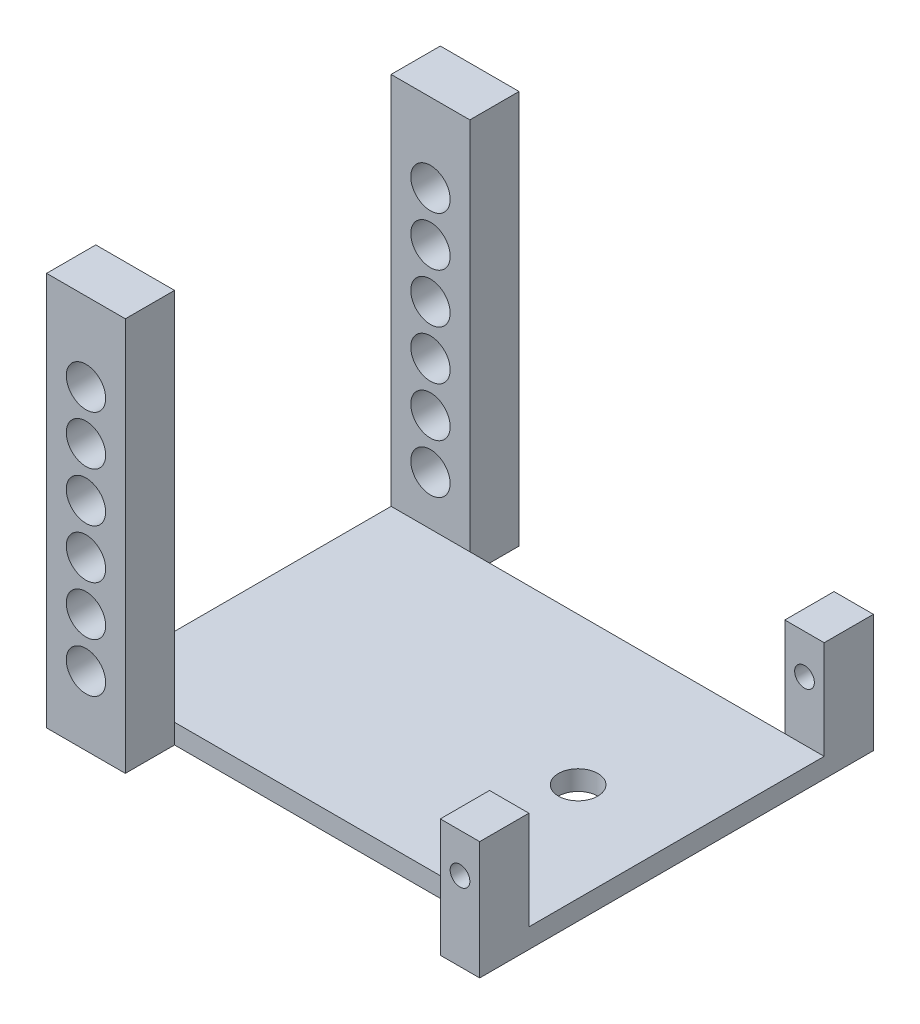
SolidWorks part; units mm, degrees
ref_plane "Front Plane" through (0, 0, 0) normal (0, 0, 1) x (1, 0, 0)
ref_plane "Top Plane" through (0, 0, 0) normal (0, 1, 0) x (1, 0, 0)
ref_plane "Right Plane" through (0, 0, 0) normal (1, 0, 0) x (0, 0, -1)
sketch "Sketch1" plane through (0, 0, 0) normal (0, 1, 0) x (1, 0, 0)
  line L1 (-100, 75) -> (100, 75)
  line L2 (-100, 75) -> (-100, -75)
  line L3 (-100, -75) -> (100, -75)
  line L4 (100, 75) -> (100, -75)
  line L5 (-100, 75) -> (100, -75) construction
  line L6 (-100, -75) -> (100, 75) construction
  point P0 (0, 0)
  dimension "D1" = 150
  dimension "D2" = 200
extrude "Boss-Extrude1" add sketch "Sketch1" along normal blind 10
sketch "Sketch2" plane through (0, 10, 0) normal (0, 1, 0) x (1, 0, 0)
  line L0 (100, -75) -> (100, 75) construction
  line L1 (-100, -75) -> (100, -75) construction
  line L2 (100, 75) -> (-100, 75) construction
  circle A0 centre (50, 0) radius 10
  point P6 (106.6698, -42.9521)
  dimension "D1" = 20
  dimension "D2" = 50
  dimension "D3" = 75
  dimension "D4" = 75
extrude "Cut-Extrude1" cut sketch "Sketch2" against normal blind 10
sketch "Sketch3" plane through (0, 0, 75) normal (0, 0, 1) x (1, 0, 0)
  line L0 (100, 0) -> (100, 60)
  line L1 (100, 60) -> (80, 60)
  line L2 (80, 60) -> (80, 0)
  line L3 (-100, 0) -> (100, 0) construction
  line L4 (80, 0) -> (100, 0)
  line L6 (-100, 200) -> (-120, 200)
  line L7 (-120, 200) -> (-120, 0)
  line L8 (-120, 0) -> (-100, 0)
  line L9 (-100, 200) -> (-80, 200)
  line L10 (-80, 200) -> (-80, 0)
  line L11 (-80, 0) -> (-100, 0)
  dimension "D1" = 20
  dimension "D2" = 60
  dimension "D3" = 200
  dimension "D4" = 20
  dimension "D5" = 20
sketch "Sketch4" plane through (-100, 0, 0) normal (-1, 0, 0) x (0, 0, 1)
  line L1 (-75, 10) -> (75, 10)
  line L2 (-75, 10) -> (-75, 0)
  line L3 (-75, 0) -> (75, 0)
  line L4 (75, 10) -> (75, 0)
  line L5 (-75, 10) -> (75, 0) construction
  line L6 (-75, 0) -> (75, 10) construction
  line L7 (-75, 10) -> (75, 10) construction
  line L8 (-75, 10) -> (-75, 0) construction
  point P0 (0, 5)
  dimension "D1" = 0
  dimension "D2" = 0
extrude "Boss-Extrude2" add sketch "Sketch4" along normal blind 20
extrude "Boss-Extrude3" add sketch "Sketch3" along normal blind 25
sketch "Sketch5" plane through (0, 0, -75) normal (0, 0, -1) x (-1, 0, 0)
  line L0 (-100, 0) -> (-100, 60)
  line L1 (-100, 60) -> (-80, 60)
  line L2 (-80, 60) -> (-80, 0)
  line L3 (-80, 0) -> (-100, 0)
  line L12 (80, 200) -> (120, 200)
  line L13 (120, 200) -> (120, 0)
  line L14 (120, 0) -> (80, 0)
  line L15 (80, 0) -> (80, 200)
  dimension "D1" = 60
extrude "Boss-Extrude4" add sketch "Sketch5" along normal blind 25
sketch "Sketch7" plane through (0, 0, -100) normal (0, 0, -1) x (-1, 0, 0)
  line L0 (-100, 0) -> (-80, 0) construction
  circle A0 centre (-90, 40) radius 5
  dimension "D1" = 10
  dimension "D2" = 40
extrude "Cut-Extrude3" cut sketch "Sketch7" against normal blind 251
sketch "Sketch9" plane through (0, 0, 100) normal (0, 0, 1) x (1, 0, 0)
  line L0 (-120, 0) -> (-80, 0) construction
  line L1 (-80, 0) -> (-80, 200) construction
  circle A0 centre (-100, 160) radius 10
  circle A1 centre (-100, 135) radius 10
  circle A2 centre (-100, 110) radius 10
  circle A3 centre (-100, 85) radius 10
  circle A5 centre (-100, 35) radius 10
  circle A6 centre (-100, 60) radius 10
  dimension "D1" = 20
  dimension "D7" = 20
  dimension "D8" = 20
  dimension "D9" = 20
  dimension "D10" = 20
  dimension "D11" = 20
  dimension "D2" = 160
  dimension "D3" = 20
  dimension "D4" = 25
  dimension "D5" = 25
  dimension "D6" = 25
  dimension "D12" = 25
  dimension "D13" = 25
extrude "Cut-Extrude4" cut sketch "Sketch9" against normal blind 241
